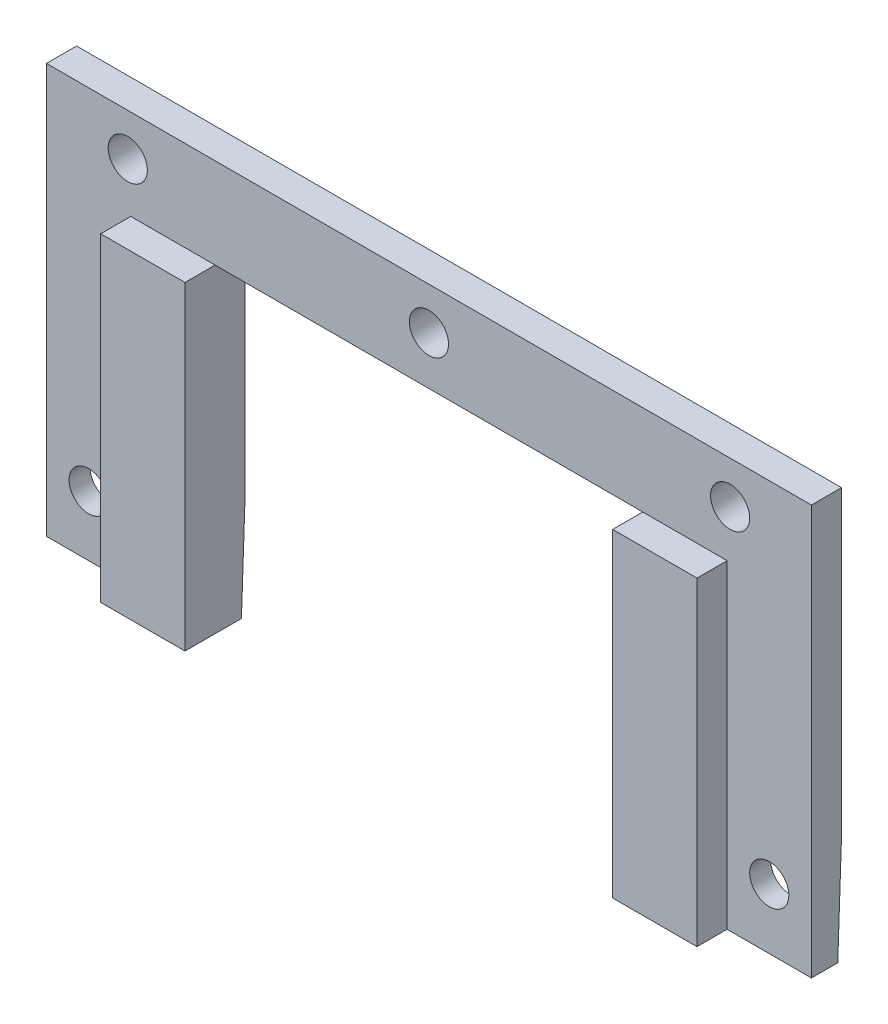
SolidWorks part; units mm, degrees
ref_plane "Front Plane" through (0, 0, 0) normal (0, 0, 1) x (1, 0, 0)
ref_plane "Top Plane" through (0, 0, 0) normal (0, 1, 0) x (1, 0, 0)
ref_plane "Right Plane" through (0, 0, 0) normal (1, 0, 0) x (0, 0, -1)
sketch "Total Station Geometry" plane through (0, 0, 0) normal (0, 0, 1) x (1, 0, 0)
  line L8 (56.5, 57) -> (34.5, 57) construction
  line L9 (-56.5, 57) -> (-63.5, 57) construction
  line L10 (56.5, 57) -> (63.5, 57) construction
  line L11 (-56.5, 57) -> (-34.5, 57) construction
  line L12 (34.5, 65) -> (34.5, 0) construction
  line L13 (34.5, 0) -> (32.5, 0) construction
  line L14 (32.5, 0) -> (32.5, 98.9949) construction
  line L15 (32.5, 98.9949) -> (-32.5, 98.9949) construction
  line L16 (-32.5, 98.9949) -> (-32.5, 0) construction
  line L17 (-32.5, 0) -> (-34.5, 0) construction
  line L18 (-34.5, 0) -> (-34.5, 65) construction
  line L19 (-34.5, 65) -> (-64.5, 65) construction
  line L20 (-64.5, 65) -> (-64.5, 0) construction
  line L21 (-34.5, 46) -> (-64.5, 46) construction
  line L22 (64.5, 0) -> (64.5, 65) construction
  line L23 (64.5, 65) -> (34.5, 65) construction
  line L24 (-32.5, 0) -> (32.5, 0) construction
  line L25 (-32.5, 0) -> (-32.5, -98.9949) construction
  line L26 (-32.5, -98.9949) -> (32.5, -98.9949) construction
  line L27 (32.5, -98.9949) -> (32.5, 0) construction
  circle A2 centre (56.5, 57) radius 5 construction
  circle A3 centre (56.5, 57) radius 6 construction
  circle A4 centre (-56.5, 57) radius 6 construction
  circle A5 centre (-56.5, 57) radius 5 construction
  point P22 (0, 98.9949)
  dimension "D4" = 65
  dimension "D7" = 1
  dimension "D8" = 10
  dimension "D9" = 8
  dimension "D10" = 8
  dimension "D2" = 113
  dimension "D3" = 7
  dimension "D11" = 197.9899
  dimension "D12" = 65
  dimension "D13" = 30
  dimension "D14" = 19
sketch "Sketch2" plane through (0, 0, 0) normal (0, 0, 1) x (1, 0, 0)
  line L0 (-63.5, 47) -> (-63.5, 115)
  line L1 (-63.5, 115) -> (63.5, 115)
  line L2 (63.5, 115) -> (63.5, 47)
  line L3 (63.5, 47) -> (35.5, 47)
  line L4 (35.5, 47) -> (35.5, 100)
  line L5 (35.5, 100) -> (-35.5, 100)
  line L6 (-35.5, 100) -> (-35.5, 47)
  line L7 (-35.5, 47) -> (-63.5, 47)
  line L8 (-34.5, 46) -> (-64.5, 46) construction
  line L9 (-64.5, 65) -> (-64.5, 0) construction
  line L10 (-34.5, 0) -> (-34.5, 65) construction
  line L11 (-50, 108) -> (50, 108) construction
  line L12 (0, 108) -> (0, 115) construction
  circle A2 centre (-50, 108) radius 3.25
  circle A3 centre (50, 108) radius 3.25
  circle A4 centre (0, 108) radius 3.25
  point P9 (0, 100)
  dimension "D6" = 8
  dimension "D8" = 6.5
  dimension "D1" = 100
  dimension "D2" = 15
  dimension "D3" = 1
  dimension "D4" = 1
  dimension "D5" = 1
  dimension "D9" = 100
extrude "Boss-Extrude2" add sketch "Sketch2" along normal blind 5
sketch "Sketch4" plane through (0, 0, 5) normal (0, 0, 1) x (1, 0, 0)
  line L0 (-63.5, 47) -> (-35.5, 47) construction
  line L1 (-49.5, 47) -> (-35.5, 47)
  line L2 (-49.5, 47) -> (-49.5, 100)
  line L3 (-49.5, 100) -> (-35.5, 100)
  line L4 (-35.5, 47) -> (-35.5, 100)
  line L5 (35.5, 47) -> (63.5, 47) construction
  line L6 (35.5, 47) -> (49.5, 47)
  line L7 (35.5, 47) -> (35.5, 100)
  line L8 (35.5, 100) -> (49.5, 100)
  line L9 (49.5, 47) -> (49.5, 100)
  line L11 (-63.5, 115) -> (-63.5, 47) construction
  line L13 (-35.5, 100) -> (35.5, 100) construction
  line L14 (-35.5, 100) -> (35.5, 100) construction
  line L15 (-35.5, 47) -> (-35.5, 100) construction
  point P17 (0, 100)
  dimension "D1" = 14
extrude "Ribs" add sketch "Sketch4" along normal blind 5
sketch "Sketch5" plane through (0, 0, 0) normal (1, 0, 0) x (0, 0, -1)
  line L1 (0, 47) -> (0, 115) construction
  line L3 (0, 47) -> (0, 65)
  line L5 (0, 65) -> (-0.6286, 47)
  line L6 (-0.6286, 47) -> (0, 47)
  dimension "D1" = 2
extrude "Angle Cut" cut sketch "Sketch5" against normal through all both and the other way through all
sketch "Sketch3" plane through (0, 93.4946, 0) normal (0, 0, 1) x (-1, 0, 0)
  circle A0 centre (56.5, 36.4946) radius 6.5
  circle A1 centre (-56.5, 36.4946) radius 6.5
  dimension "D1" = 13
extrude "Counterbore" cut sketch "Sketch3" along normal blind 1.5
sketch "Sketch6" plane through (0, 129.8899, 0) normal (0, 0, 1) x (-1, 0, 0)
  circle A0 centre (-56.5, 72.8899) radius 3.25
  circle A1 centre (56.5, 72.8899) radius 3.25
  dimension "D1" = 6.5
extrude "Bolt thru-hole" cut sketch "Sketch6" along normal through all
